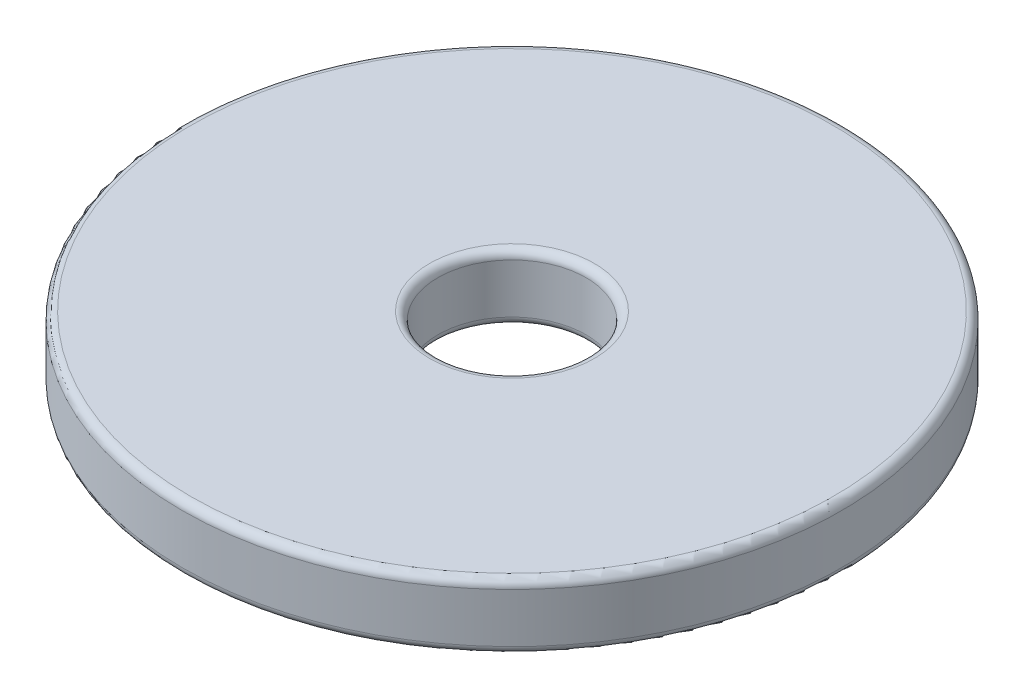
SolidWorks part; units mm, degrees
ref_plane "Front Plane" through (0, 0, 0) normal (0, 0, 1) x (1, 0, 0)
ref_plane "Top Plane" through (0, 0, 0) normal (0, 1, 0) x (1, 0, 0)
ref_plane "Right Plane" through (0, 0, 0) normal (1, 0, 0) x (0, 0, -1)
sketch "Sketch1" plane through (0, 0, 0) normal (0, 1, 0) x (1, 0, 0)
  circle A0 centre (0, 0) radius 10
  circle A1 centre (0, 0) radius 2.25
  dimension "D1" = 20
  dimension "D2" = 4.5
extrude "Boss-Extrude1" add sketch "Sketch1" along normal blind 2
fillet "Fillet1" radius 0.25 4 edges at (0, 0, 2.25) (0, 2, 2.25) (0, 0, 10) (0, 2, 10)
move or copy body "Body-Convert to Mesh Body1" [suppressed] bodies to move or copy 101 copy no translate (0, 0, 0)
